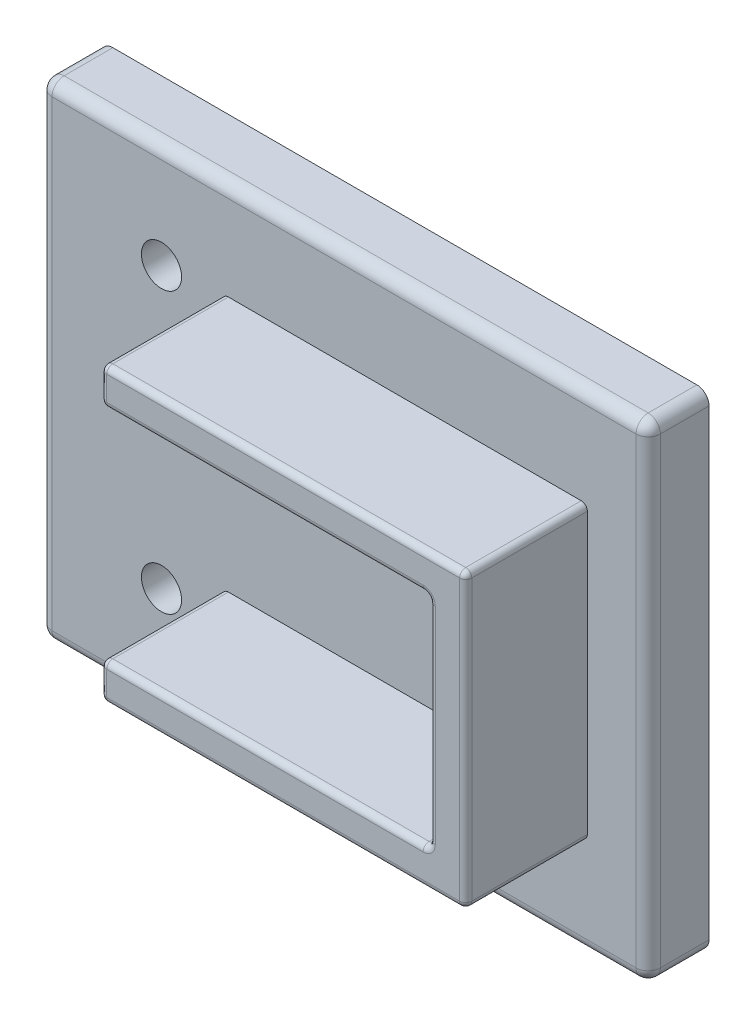
SolidWorks part; units mm, degrees
ref_plane "前视基准面" through (0, 0, 0) normal (0, 0, 1) x (1, 0, 0)
ref_plane "上视基准面" through (0, 0, 0) normal (0, 1, 0) x (1, 0, 0)
ref_plane "右视基准面" through (0, 0, 0) normal (1, 0, 0) x (0, 0, -1)
other "Configuration Table"
sketch "草图2" plane through (0, 0, 0) normal (0, 0, 1) x (1, 0, 0)
  line L0 (88, 39) -> (88, -19) construction
  line L1 (78, 30) -> (28, 30)
  line L2 (78, 30) -> (78, -10)
  line L3 (78, -10) -> (28, -10)
  line L4 (28, 30) -> (28, -10)
  line L5 (88, 10) -> (-32, 10) construction
  line L6 (-32, -19) -> (-32, 39) construction
  dimension "D1" = 40
  dimension "D2" = 50
  dimension "D3" = 10
extrude "凸台-拉伸1" add sketch "草图2" along normal blind 5
sketch "草图5" plane through (0, -10, 0) normal (0, -1, 0) x (1, 0, 0)
  line L0 (73, 5) -> (73, 15)
  line L1 (28, 5) -> (78, 5) construction
  line L2 (73, 15) -> (43, 15)
  line L3 (43, 15) -> (43, 5)
  line L4 (43, 5) -> (73, 5)
  line L5 (78, 5) -> (78, 0) construction
  dimension "D1" = 30
  dimension "D2" = 10
  dimension "D3" = 90
  dimension "D4" = 5
extrude "凸台-拉伸2" add sketch "草图5" against normal blind 3 from offset 8 offset against normal yes
sketch "草图6" plane through (0, 30, 0) normal (0, 1, 0) x (1, 0, 0)
  line L4 (73, -15) -> (73, -5)
  line L5 (43, -15) -> (73, -15)
  line L6 (43, -5) -> (43, -15)
  line L7 (73, -5) -> (43, -5)
  line L8 (73, -15) -> (73, -5)
  line L9 (43, -15) -> (73, -15)
  line L10 (43, -5) -> (43, -15)
  line L11 (73, -5) -> (43, -5)
  dimension "D1" = 0
extrude "凸台-拉伸3" add sketch "草图6" against normal blind 3 from offset 8 offset against normal yes
sketch "草图7" plane through (0, 0, 0) normal (0, 0, -1) x (-1, 0, 0)
  circle A4 centre (-63, 10) radius 1.65
  circle A5 centre (-38, -1.5) radius 1.65
  circle A6 centre (-38, 21.5) radius 1.65
  dimension "D1" = 3.3
extrude "切除-拉伸1" cut sketch "草图7" against normal up to next
fillet "圆角3" radius 1 8 edges at (53, -10, 5) (28, 10, 5) (53, 30, 5) (78, 10, 5) (28, -10, 2.5) (28, 30, 2.5) (78, 30, 2.5) (78, -10, 2.5)
sketch "草图8" plane through (73, 0, 0) normal (1, 0, 0) x (0, 0, -1)
  line L1 (-15, 19) -> (-5, 19)
  line L2 (-15, 19) -> (-15, -2)
  line L3 (-15, -2) -> (-5, -2)
  line L4 (-5, 19) -> (-5, -2)
extrude "凸台-拉伸4" add sketch "草图8" against normal blind 3
fillet "圆角4" radius 0.5 16 edges at (56.5, 19, 15) (43, 20.5, 15) (58, 22, 15) (73, 10, 15) (58, -2, 15) (43, -0.5, 15) (56.5, 1, 15) (70, 10, 15) (70, 1, 10) (43, 1, 10) (43, -2, 10) (73, 22, 10) (43, 22, 10) (43, 19, 10) (70, 19, 10) (73, -2, 10)
